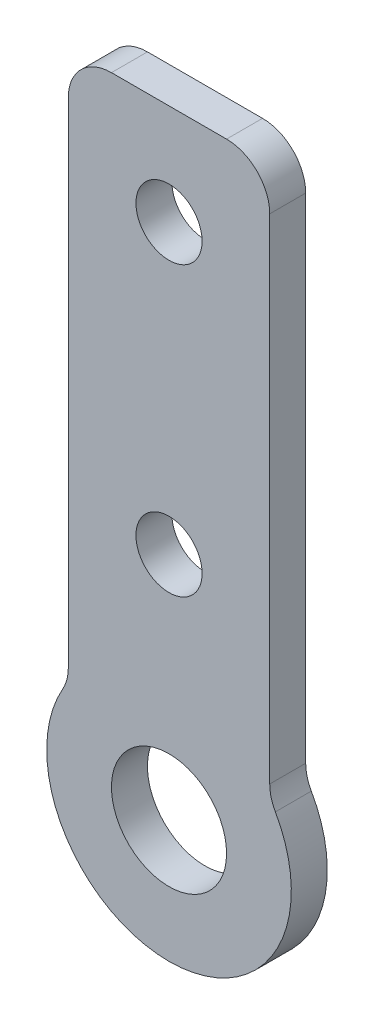
SolidWorks part; units mm, degrees
ref_plane "前视基准面" through (0, 0, 0) normal (0, 0, 1) x (1, 0, 0)
ref_plane "上视基准面" through (0, 0, 0) normal (0, 1, 0) x (1, 0, 0)
ref_plane "右视基准面" through (0, 0, 0) normal (1, 0, 0) x (0, 0, -1)
sketch "草图1" plane through (0, 0, 0) normal (0, 0, 1) x (1, 0, 0)
  line L0 (-7, 4.8218) -> (-7, 43)
  line L1 (-7, 43) -> (7, 43)
  line L2 (7, 43) -> (7, 4.8218)
  arc A0 (-7, 4.8218) -> (7, 4.8218) centre (0, 0) ccw
  circle A1 centre (0, 0) radius 4
  circle A2 centre (0, 36) radius 2.3
  circle A3 centre (0, 16) radius 2.3
  point P7 (0, 43)
  point P12 (0, 0)
  dimension "D1" = 17
  dimension "D4" = 8
  dimension "D5" = 20
  dimension "D6" = 16
  dimension "D7" = 4.6
  dimension "D2" = 14
  dimension "D3" = 43
extrude "凸台-拉伸1" add sketch "草图1" along normal mid plane 2.5
fillet "圆角1" radius 3 4 edges at (7, 43, 0) (-7, 43, 0) (-7, 4.8218, 0) (7, 4.8218, 0)
